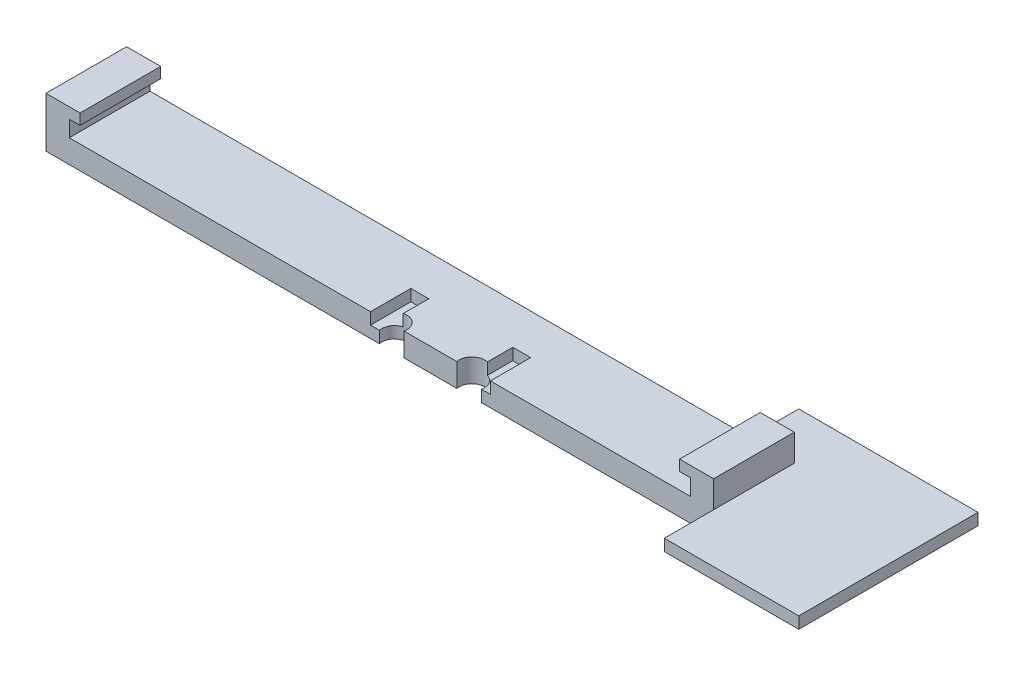
SolidWorks part; units mm, degrees
ref_plane "Front Plane" through (0, 0, 0) normal (0, 0, 1) x (1, 0, 0)
ref_plane "Top Plane" through (0, 0, 0) normal (0, 1, 0) x (1, 0, 0)
ref_plane "Right Plane" through (0, 0, 0) normal (1, 0, 0) x (0, 0, -1)
sketch "Sketch1" plane through (0, 0, 0) normal (0, 1, 0) x (1, 0, 0)
  line L0 (-42.3164, 2.159) -> (-79.5037, 2.159) construction
  line L1 (0, 0) -> (-88.011, 0)
  line L2 (0, 0) -> (0, 11.43)
  line L3 (0, 11.43) -> (-88.011, 11.43)
  line L4 (-88.011, 0) -> (-88.011, 11.43)
  line L5 (-79.5037, 2.159) -> (-62.4529, 2.159) construction
  line L6 (-44.0944, 0.381) -> (-44.0944, 5.9822) construction
  line L7 (-29.5656, 0.381) -> (-29.5656, 8.1925) construction
  circle A0 centre (-42.3164, 0.381) radius 1.778
  circle A1 centre (-31.3436, 0.381) radius 1.778
  dimension "D3" = 3.556
  dimension "D4" = 3.556
  dimension "D6" = 0
  dimension "D1" = 88.011
  dimension "D2" = 11.43
  dimension "D5" = 9.271
  dimension "D7" = 14.5288
  dimension "D8" = 29.5656
extrude "Boss-Extrude1" add sketch "Sketch1" along normal blind 3.302 contours A1 L1 L2 L3 L4 A0
sketch "Sketch2" plane through (0, 0, 0) normal (1, 0, 0) x (0, 0, -1)
  line L0 (0, 3.302) -> (11.43, 3.302) construction
  line L1 (0, 0) -> (11.43, 0)
  line L2 (0, 0) -> (0, 7.112)
  line L3 (0, 7.112) -> (11.43, 7.112)
  line L4 (11.43, 0) -> (11.43, 7.112)
  line L5 (11.43, 3.302) -> (11.43, 0) construction
  dimension "D1" = 3.81
  dimension "D2" = 0
extrude "Boss-Extrude2" add sketch "Sketch2" along normal blind 3.302
sketch "Sketch3" plane through (-88.011, 0, 0) normal (-1, 0, 0) x (0, 0, 1)
  line L1 (-11.43, 0) -> (0, 0)
  line L2 (-11.43, 0) -> (-11.43, 7.112)
  line L3 (-11.43, 7.112) -> (0, 7.112)
  line L4 (0, 0) -> (0, 7.112)
extrude "Boss-Extrude3" add sketch "Sketch3" along normal blind 3.302
sketch "Sketch4" plane through (0, 7.112, 0) normal (0, 1, 0) x (1, 0, 0)
  line L0 (0, 11.43) -> (-88.011, 11.43) construction
  line L1 (-88.011, 0) -> (-86.487, 0)
  line L2 (-88.011, 0) -> (-88.011, 11.43)
  line L3 (-88.011, 11.43) -> (-86.487, 11.43)
  line L4 (-86.487, 0) -> (-86.487, 11.43)
  dimension "D1" = 1.524
extrude "Boss-Extrude4" add sketch "Sketch4" against normal blind 1.524
sketch "Sketch5" plane through (0, 7.112, 0) normal (0, 1, 0) x (1, 0, 0)
  line L0 (0, 11.43) -> (-88.011, 11.43) construction
  line L1 (0, 0) -> (-1.524, 0)
  line L2 (0, 0) -> (0, 11.43)
  line L3 (0, 11.43) -> (-1.524, 11.43)
  line L4 (-1.524, 0) -> (-1.524, 11.43)
  dimension "D1" = 1.524
extrude "Boss-Extrude5" add sketch "Sketch5" against normal blind 1.524
sketch "Sketch6" plane through (0, 3.302, 0) normal (0, 1, 0) x (1, 0, 0)
  line L0 (-2.54, 7.493) -> (-2.54, 9.0724) construction
  line L1 (-2.54, 9.0724) -> (-2.54, 3.3849) construction
  line L2 (0, 0) -> (0, 11.43) construction
  line L3 (-85.471, 7.493) -> (-85.471, 9.0724) construction
  line L4 (-85.471, 9.0724) -> (-85.471, 2.3439) construction
  line L5 (-88.011, 0) -> (-88.011, 11.43) construction
  line L6 (-84.074, 8.89) -> (-73.4902, 8.89) construction
  line L7 (0, 11.43) -> (-88.011, 11.43) construction
  circle A1 centre (-84.074, 7.493) radius 1.397
  circle A2 centre (-3.937, 7.493) radius 1.397
  dimension "D1" = 2.794
  dimension "D2" = 2.794
  dimension "D3" = 0
  dimension "D4" = 2.54
  dimension "D5" = 2.54
  dimension "D6" = 2.54
sketch "Sketch7" plane through (0, 3.302, 0) normal (0, 1, 0) x (1, 0, 0)
  line L0 (-44.0531, 0) -> (-88.011, 0) construction
  line L1 (-45.3231, 0) -> (-42.7831, 0)
  line L2 (-45.3231, 0) -> (-45.3231, 5.715)
  line L3 (-45.3231, 5.715) -> (-42.7831, 5.715)
  line L4 (-42.7831, 0) -> (-42.7831, 5.715)
  line L5 (-40.5797, 0) -> (-40.5797, 11.43) construction
  line L6 (0, 11.43) -> (-88.011, 11.43) construction
  line L8 (-30.8769, 5.715) -> (-28.3369, 5.715)
  line L9 (-30.8769, 5.715) -> (-30.8769, 0)
  line L10 (-30.8769, 0) -> (-28.3369, 0)
  line L11 (-28.3369, 5.715) -> (-28.3369, 0)
  line L12 (0, 0) -> (-29.6069, 0) construction
  point P4 (-44.0531, 0)
  point P14 (-40.5797, 5.715)
  point P19 (-29.6069, 0)
  dimension "D1" = 0
  dimension "D2" = 0
  dimension "D3" = 0
  dimension "D4" = 2.54
  dimension "D5" = 0
  dimension "D6" = 0
extrude "Cut-Extrude1" cut sketch "Sketch7" against normal blind 1.651
sketch "Sketch9" plane through (0, 0, 0) normal (0, -1, 0) x (1, 0, 0)
  line L0 (-3.048, 6.985) -> (22.352, -18.415) construction
  line L1 (-3.048, -18.415) -> (22.352, -18.415)
  line L2 (-3.048, -18.415) -> (-3.048, 6.985)
  line L3 (-3.048, 6.985) -> (22.352, 6.985)
  line L4 (22.352, -18.415) -> (22.352, 6.985)
  line L5 (3.302, 0) -> (3.302, -11.43) construction
  line L6 (-3.048, -18.415) -> (22.352, 6.985) construction
  line L7 (3.302, 0) -> (3.302, 6.985)
  point P6 (3.302, -5.715)
  point P7 (9.652, -5.715)
  line M10 (-91.313, -11.43) -> (3.302, -11.43)
  line M11 (3.302, -11.43) -> (3.302, 0)
  dimension "D1" = 25.4
  dimension "D2" = 25.4
  dimension "D3" = 0
  dimension "D4" = 19.05
extrude "Boss-Extrude8" add sketch "Sketch9" along normal blind 1.651 from surface at -3.302 contours L7 L2 L1 L4 L3 M11 M10 starting at face at (-38.8801, 3.302, -3.6539)
